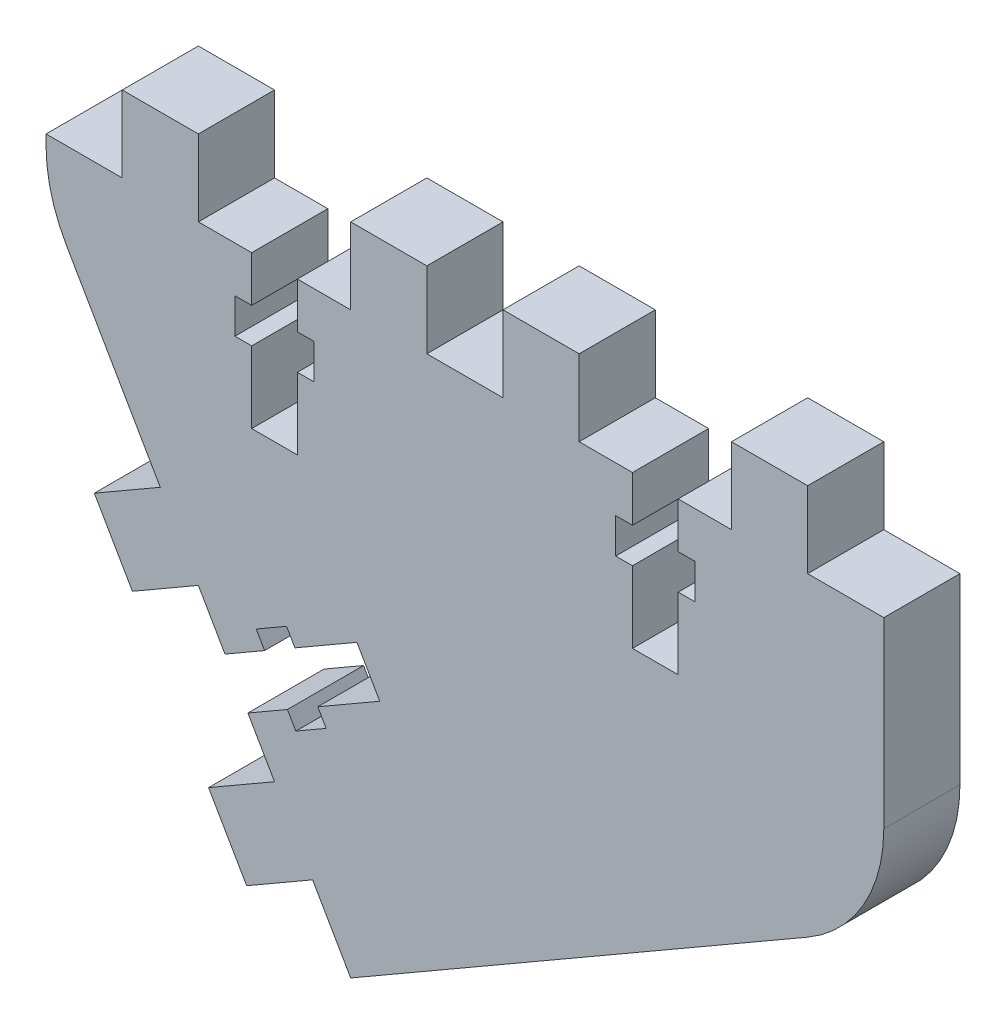
SolidWorks part; units mm, degrees
ref_plane "Plan de face" through (0, 0, 0) normal (0, 0, 1) x (1, 0, 0)
ref_plane "Plan de dessus" through (0, 0, 0) normal (0, 1, 0) x (1, 0, 0)
ref_plane "Plan de droite" through (0, 0, 0) normal (1, 0, 0) x (0, 0, -1)
sketch "Esquisse1" plane through (0, 0, 0) normal (0, 0, 1) x (1, 0, 0)
  line L0 (0, 0) -> (35.8133, 0) construction
  line L1 (15, 0) -> (15, -30.9586) construction
  line L2 (-5, 8.6603) -> (-7.5, 12.9904)
  line L3 (-12.5, 21.6506) -> (-12.5, 25)
  line L4 (-7.5, 12.9904) -> (-12.5, 21.6506)
  line L5 (12.5, 25) -> (17.5, 25)
  line L6 (5, -8.6603) -> (7.5, -12.9904)
  line L7 (7.5, -12.9904) -> (42.5, 7.2169)
  line L8 (42.5, 7.2169) -> (42.5, 25)
  line L9 (42.5, 25) -> (37.5, 25)
  line L10 (-7.5, 25) -> (-12.5, 25)
  line B0 (1.2981, 3.7517) -> (3.2899, 4.9017)
  line B1 (5.3399, 1.351) -> (9.4103, 3.701)
  line B2 (7.9103, 6.299) -> (3.8399, 3.949)
  line B3 (3.2899, 4.9017) -> (3.8399, 3.949)
  line B4 (0, 0) -> (9.7175, 5.6104) construction
  line B5 (-0.75, 1.299) -> (-2.5, 4.3301)
  line B6 (-6.8301, 1.8301) -> (-9.3301, 6.1603)
  line B7 (-9.3301, 6.1603) -> (-5, 8.6603)
  line B8 (-6.8301, 1.8301) -> (-2.5, 4.3301)
  line B9 (0.75, -1.299) -> (2.5, -4.3301)
  line B10 (2.5, -4.3301) -> (-1.8301, -6.8301)
  line B11 (-1.8301, -6.8301) -> (0.6699, -11.1603)
  line B12 (0.6699, -11.1603) -> (5, -8.6603)
  line B13 (-0.75, 1.299) -> (0.75, -1.299) construction
  line B14 (0.75, -1.299) -> (3.3481, 0.201)
  line B15 (5.3399, 1.351) -> (5.8899, 0.3983)
  line B16 (3.8981, -0.7517) -> (3.3481, 0.201)
  line B17 (9.4103, 3.701) -> (7.9103, 6.299)
  line B18 (1.8481, 2.799) -> (1.2981, 3.7517)
  line B19 (5.8899, 0.3983) -> (3.8981, -0.7517)
  line B20 (1.8481, 2.799) -> (-0.75, 1.299)
  line B21 (8.6603, 5) -> (0, 0) construction
  line B22 (30.1, 22) -> (30.1, 19.7)
  line B23 (26, 19.7) -> (26, 15)
  line B24 (29, 15) -> (29, 19.7)
  line B25 (30.1, 19.7) -> (29, 19.7)
  line B26 (27.5, 25) -> (27.5, 13.7792) construction
  line B27 (29, 25) -> (32.5, 25)
  line B28 (32.5, 30) -> (37.5, 30)
  line B29 (37.5, 30) -> (37.5, 25)
  line B30 (32.5, 30) -> (32.5, 25)
  line B31 (26, 25) -> (22.5, 25)
  line B32 (22.5, 25) -> (22.5, 30)
  line B33 (22.5, 30) -> (17.5, 30)
  line B34 (17.5, 30) -> (17.5, 25)
  line B35 (29, 25) -> (26, 25) construction
  line B36 (26, 25) -> (26, 22)
  line B37 (26, 19.7) -> (24.9, 19.7)
  line B38 (24.9, 22) -> (26, 22)
  line B39 (26, 15) -> (29, 15)
  line B40 (29, 22) -> (30.1, 22)
  line B41 (24.9, 19.7) -> (24.9, 22)
  line B42 (29, 22) -> (29, 25)
  line B43 (27.5, 15) -> (27.5, 25) construction
  line B44 (-0.1, 22) -> (-0.1, 19.7)
  line B45 (4, 19.7) -> (4, 15)
  line B46 (1, 15) -> (1, 19.7)
  line B47 (-0.1, 19.7) -> (1, 19.7)
  line B48 (2.5, 25) -> (2.5, 13.7792) construction
  line B49 (1, 25) -> (-2.5, 25)
  line B50 (-2.5, 30) -> (-7.5, 30)
  line B51 (-7.5, 30) -> (-7.5, 25)
  line B52 (-2.5, 30) -> (-2.5, 25)
  line B53 (4, 25) -> (7.5, 25)
  line B54 (7.5, 25) -> (7.5, 30)
  line B55 (7.5, 30) -> (12.5, 30)
  line B56 (12.5, 30) -> (12.5, 25)
  line B57 (1, 25) -> (4, 25) construction
  line B58 (4, 25) -> (4, 22)
  line B59 (4, 19.7) -> (5.1, 19.7)
  line B60 (5.1, 22) -> (4, 22)
  line B61 (4, 15) -> (1, 15)
  line B62 (1, 22) -> (-0.1, 22)
  line B63 (5.1, 19.7) -> (5.1, 22)
  line B64 (1, 22) -> (1, 25)
  line B65 (2.5, 15) -> (2.5, 25) construction
  dimension "D1" = 5
  dimension "D2" = 60
  dimension "D3" = 5
  dimension "D4" = 25
  dimension "D5" = 15
sketch_block_instance "Insert M3 plots ep 5mm-1"
sketch_block "Insert M3 plots ep 5mm" parameters "D1"=10, "D2"=5, "D3"=5
sketch_block_instance "Decoupe Insert M3-4"
sketch_block "Decoupe Insert M3" parameters "D1"=5.2, "D2"=3, "D3"=2.3, "D4"=3, "D5"=10
sketch_block_instance "Insert M3 plots ep 5mm-3"
sketch_block_instance "Insert M3 plots ep 5mm-4"
extrude "Boss.-Extru.1" add sketch "Esquisse1" along normal blind 5
fillet "Congé1" radius 10 2 edges at (-12.5, 21.6506, 2.5) (42.5, 7.2169, 2.5)
